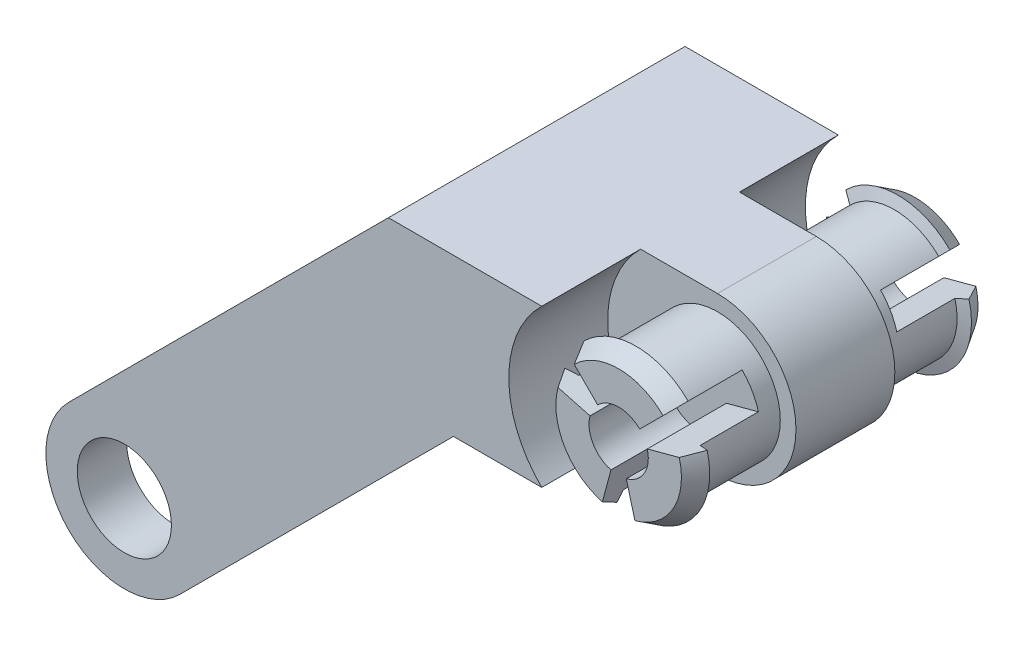
SolidWorks part; units mm, degrees
ref_plane "Alzado" through (0, 0, 0) normal (0, 0, 1) x (1, 0, 0)
ref_plane "Planta" through (0, 0, 0) normal (0, 1, 0) x (1, 0, 0)
ref_plane "Vista lateral" through (0, 0, 0) normal (1, 0, 0) x (0, 0, -1)
sketch "Croquis1" plane through (0, 0, 0) normal (0, 0, 1) x (1, 0, 0)
  line L0 (-2.8063, 2.8063) -> (13.3561, 18.9688)
  line L1 (13.3561, 18.9688) -> (25, 18.9688)
  line L2 (25, 18.9688) -> (25, 11.0312)
  line L3 (25, 11.0312) -> (16.6439, 11.0312)
  line L4 (16.6439, 11.0312) -> (2.8063, -2.8063)
  line L5 (0, -3.9687) -> (16.1518, -3.9687) construction
  line L6 (0, 0) -> (0, 22.779) construction
  line L7 (18.0887, 15) -> (31.0225, 15) construction
  line L8 (-11.9933, 0) -> (35.7455, 0) construction
  circle A0 centre (0, 0) radius 3.9687
  circle A1 centre (25, 15) radius 3.9688
  dimension "D1" = 7.9375
  dimension "D3" = 25
  dimension "D2" = 45
  dimension "D4" = 15
extrude "Saliente-Extruir1" add sketch "Croquis1" along normal mid plane 15 contours A0 | A1 L1 L0 A0 L4 L3 | L2 A1 | L2 A1
sketch "Croquis2" plane through (-2.8063, 2.8063, 0) normal (-0.7071, 0.7071, 0) x (0, 0, 1)
  line L0 (0, 3.5718) -> (0, -6.6545) construction
  line L1 (-7.5, 0) -> (7.5, 0) construction
  line L2 (-7.5, 0) -> (-7.5, -3.9688) construction
  line L3 (-7.5, -3.9688) -> (7.5, -3.9688) construction
  line L4 (7.5, 0) -> (7.5, -3.9688) construction
  line L5 (-5, 0) -> (-2.5, 0)
  line L6 (-5, 0) -> (-5, -3.9688)
  line L7 (-5, -3.9688) -> (-2.5, -3.9688)
  line L8 (-2.5, 0) -> (-2.5, -3.9688)
  line L9 (5, -3.9688) -> (2.5, -3.9688)
  line L10 (2.5, 0) -> (2.5, -3.9688)
  line L11 (5, 0) -> (2.5, 0)
  line L12 (5, 0) -> (5, -3.9688)
  dimension "D1" = 2.5
  dimension "D2" = 5
extrude "Cortar-Extruir1" cut sketch "Croquis2" against normal blind 15
sketch "Croquis4" plane through (0, 0, 7.5) normal (0, 0, 1) x (1, 0, 0)
  circle A0 centre (0, 0) radius 2.3813
  dimension "D1" = 4.7625
extrude "Cortar-Extruir2" cut sketch "Croquis4" against normal blind 15
sketch "Croquis5" plane through (0, 0, 7.5) normal (0, 0, 1) x (1, 0, 0)
  circle A0 centre (25, 15) radius 5.5562
  dimension "D1" = 11.1125
extrude "Cortar-Extruir3" cut sketch "Croquis5" against normal blind 5
mirror "Simetría1" about plane through (0, 0, 0) normal (0, 0, 1) of "Cortar-Extruir3"
sketch "Croquis7" plane through (0, 0, -2.5) normal (0, 0, -1) x (-1, 0, 0)
  circle A0 centre (-25, 15) radius 0.5
  dimension "D1" = 1
ref_plane "Plano1" through (25, 0, 0) normal (1, 0, 0) x (0, 0, -1)
sketch "Croquis8" plane through (25, 0, 0) normal (1, 0, 0) x (0, 0, -1)
  line L0 (2.5, 15) -> (4.5, 15) construction
  line L1 (2.5, 14.5) -> (2.5, 15.5) construction
  line L2 (2.5, 11.0312) -> (2.5, 18.9688) construction
  line L3 (2.5, 11.825) -> (7.5, 11.825) construction
  line L4 (2.5, 11.825) -> (2.5, 18.175) construction
  line L5 (2.5, 18.175) -> (7.5, 18.175) construction
  line L6 (7.5, 11.825) -> (7.5, 18.175) construction
  line L7 (2.5, 16.5) -> (7.5, 16.5)
  line L8 (2.5, 16.5) -> (2.5, 18.175)
  line L9 (2.5, 18.175) -> (6.4413, 18.175)
  line L10 (6.4413, 18.175) -> (6.62, 18.725)
  line L11 (6.62, 18.725) -> (7.5, 18.175)
  line L12 (7.5, 18.175) -> (7.5, 16.5)
  line L13 (3.5, 16.5) -> (3.5, 15)
  line L14 (3.5, 15) -> (2.5, 15)
  line L15 (2.5, 15) -> (2.5, 16.5)
  line L16 (3.5, 16.5) -> (2.5, 16.5)
  line L18 (7.9101, 18.725) -> (6.1422, 18.725) construction
  line L19 (7.5, 11.0312) -> (7.5, 18.9688) construction
  point P10 (7.5, 15)
  dimension "D1" = 5
  dimension "D2" = 6.35
  dimension "D3" = 0.55
  dimension "D4" = 1.5
  dimension "D5" = 72
  dimension "D6" = 1
  dimension "D7" = 0.88
revolve "Revolución1" add sketch "Croquis8" angle 360 about L0
sketch "Croquis9" plane through (0, 0, -7.5) normal (0, 0, -1) x (-1, 0, 0)
  line L0 (-25, 15) -> (-25, 10.275) construction
  line L3 (-25, 15) -> (-26.2229, 10.436)
  line L4 (-25, 15) -> (-23.7771, 10.436)
  line L5 (-25, 15) -> (-29.564, 16.2229)
  line L6 (-25, 15) -> (-28.3411, 18.3411)
  line L7 (-25, 15) -> (-21.6589, 18.3411)
  line L8 (-25, 15) -> (-20.436, 16.2229)
  arc A1 (-28.3411, 18.3411) -> (-29.564, 16.2229) centre (-25, 15) ccw
  arc A4 (-20.436, 16.2229) -> (-21.6589, 18.3411) centre (-25, 15) ccw
  circle A6 centre (-25, 15) radius 4.725
  arc A7 (-26.2229, 10.436) -> (-23.7771, 10.436) centre (-25, 15) ccw
  point P10 (-25, 15)
  dimension "D3" = 1
  dimension "D2" = 3
  dimension "D1" = 15
extrude "Cortar-Extruir6" cut sketch "Croquis9" against normal blind 4 contours L6 A1 L5 L8 | L3 A7 L4
mirror "Simetría2" about plane through (0, 0, 0) normal (0, 0, 1) of "Cortar-Extruir6", "Revolución1"
sketch "Croquis10" plane through (0, 0, 0) normal (0, 0, 1) x (1, 0, 0)
  line L0 (16.6439, 11.0312) -> (2.8063, -2.8063) construction
  line L1 (0, -1.4165) -> (0, 9.0296) construction
  circle A0 centre (10.5244, 4.9118) radius 4
  circle A1 centre (10.5244, 4.9118) radius 1.5
  dimension "D1" = 8
  dimension "D2" = 10.5244
  dimension "D3" = 2.5
extrude "Cortar-Extruir7" cut sketch "Croquis10" against normal mid plane 3
